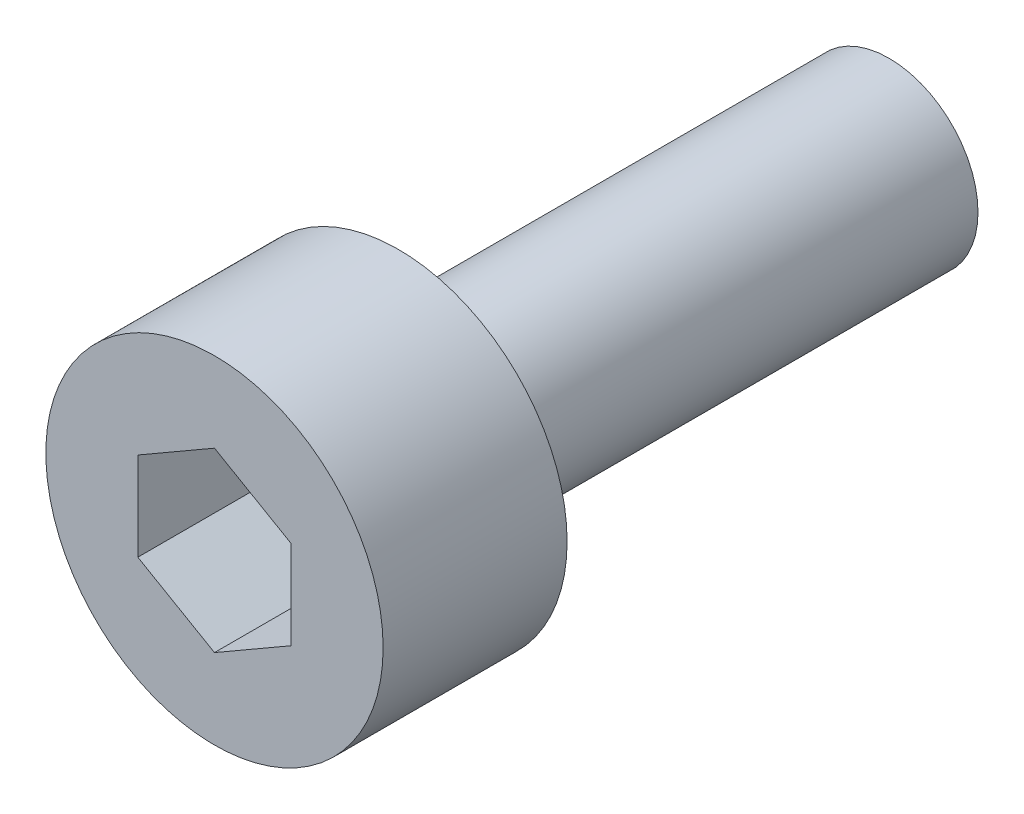
SolidWorks part; units mm, degrees
ref_plane "前视基准面" through (0, 0, 0) normal (0, 0, 1) x (1, 0, 0)
ref_plane "上视基准面" through (0, 0, 0) normal (0, 1, 0) x (1, 0, 0)
ref_plane "右视基准面" through (0, 0, 0) normal (1, 0, 0) x (0, 0, -1)
other "Configuration Table"
sketch "草图1" plane through (0, 0, 0) normal (0, 0, 1) x (1, 0, 0)
  circle A0 centre (0, 0) radius 1.45
extrude "Shank_threads_simplified" add sketch "草图1" against normal blind 8
sketch "草图2" plane through (0, 0, 0) normal (0, 0, 1) x (1, 0, 0)
  circle A0 centre (0, 0) radius 2.75
extrude "Socket_head" add sketch "草图2" along normal blind 3
ref_plane "Plane_z_3_2" through (0, 0, 3) normal (0, 0, 1) x (1, 0, 0)
sketch "草图3" plane through (0, 0, 3) normal (0, 0, 1) x (1, 0, 0)
  line L0 (1.25, 0.7217) -> (0, 1.4434)
  line L1 (0, 1.4434) -> (-1.25, 0.7217)
  line L2 (-1.25, 0.7217) -> (-1.25, -0.7217)
  line L3 (-1.25, -0.7217) -> (0, -1.4434)
  line L4 (0, -1.4434) -> (1.25, -0.7217)
  line L5 (1.25, -0.7217) -> (1.25, 0.7217)
extrude "Hex_socket" cut sketch "草图3" against normal blind 1.95
